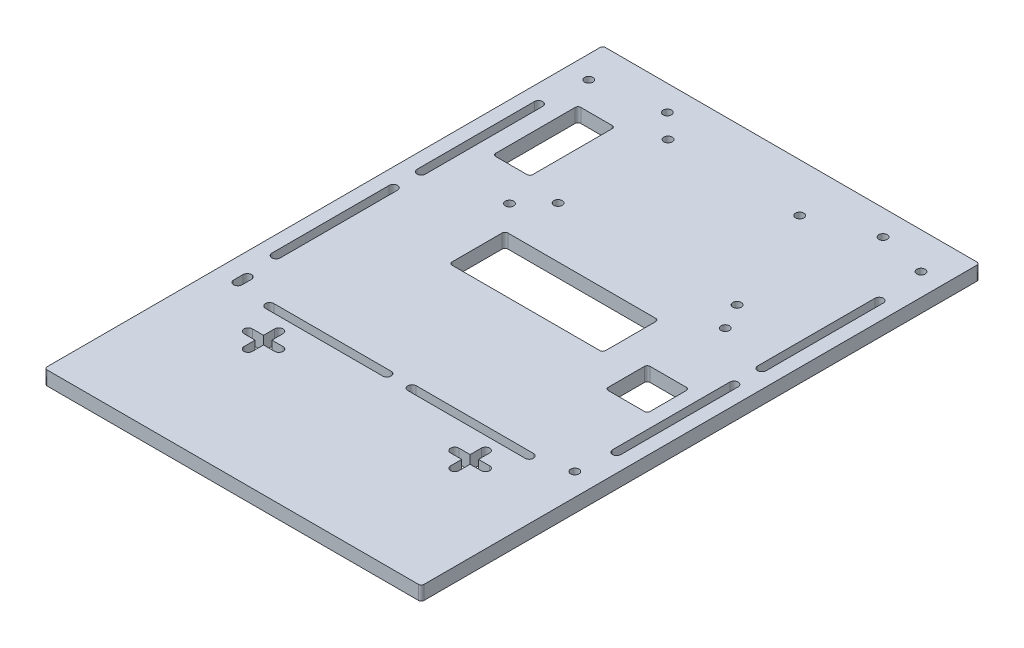
SolidWorks part; units mm, degrees
ref_plane "Front Plane" through (0, 0, 0) normal (0, 0, 1) x (1, 0, 0)
ref_plane "Top Plane" through (0, 0, 0) normal (0, 1, 0) x (1, 0, 0)
ref_plane "Right Plane" through (0, 0, 0) normal (1, 0, 0) x (0, 0, -1)
sketch "Sketch1" plane through (0, 0, 0) normal (0, 1, 0) x (1, 0, 0)
  line L1 (-67.4426, -147.7459) -> (65.5574, -147.7459)
  line L2 (-68.4426, -146.7459) -> (-68.4426, 51.2541)
  line L3 (-67.4426, 52.2541) -> (65.5574, 52.2541)
  line L4 (66.5574, -146.7459) -> (66.5574, 51.2541)
  arc A0 (-68.4426, -146.7459) -> (-67.4426, -147.7459) centre (-67.4426, -146.7459) ccw
  arc A1 (66.5574, -146.7459) -> (65.5574, -147.7459) centre (65.5574, -146.7459) cw
  arc A2 (66.5574, 51.2541) -> (65.5574, 52.2541) centre (65.5574, 51.2541) ccw
  arc A3 (-68.4426, 51.2541) -> (-67.4426, 52.2541) centre (-67.4426, 51.2541) cw
  point P7 (-68.4426, -147.7459)
  point P12 (66.5574, 52.2541)
  point P15 (-68.4426, 52.2541)
  dimension "D3" = 1
  dimension "D1" = 135
  dimension "D2" = 200
extrude "Boss-Extrude1" add sketch "Sketch1" along normal blind 5
sketch "Sketch2" plane through (0, 5, 0) normal (0, 1, 0) x (1, 0, 0)
  line L0 (60.0574, -71.2459) -> (60.0574, -29.2459) construction
  line L1 (58.5574, -71.2459) -> (58.5574, -29.2459)
  line L2 (61.5574, -71.2459) -> (61.5574, -29.2459)
  line L3 (66.5574, -146.7459) -> (66.5574, 51.2541) construction
  line L4 (65.5574, 52.2541) -> (-67.4426, 52.2541) construction
  line L5 (60.0574, -19.2459) -> (60.0574, 22.7541) construction
  line L8 (58.5574, -19.2459) -> (58.5574, 22.7541)
  line L10 (61.5574, -19.2459) -> (61.5574, 22.7541)
  line L13 (-61.9426, -71.2459) -> (-61.9426, -29.2459) construction
  line L14 (-60.4426, -71.2459) -> (-60.4426, -29.2459)
  line L15 (-63.4426, -71.2459) -> (-63.4426, -29.2459)
  line L16 (-61.9426, -19.2459) -> (-61.9426, 22.7541) construction
  line L17 (-60.4426, -19.2459) -> (-60.4426, 22.7541)
  line L18 (-63.4426, -19.2459) -> (-63.4426, 22.7541)
  arc A0 (58.5574, -71.2459) -> (61.5574, -71.2459) centre (60.0574, -71.2459) ccw
  arc A1 (61.5574, -29.2459) -> (58.5574, -29.2459) centre (60.0574, -29.2459) ccw
  arc A8 (58.5574, -19.2459) -> (61.5574, -19.2459) centre (60.0574, -19.2459) ccw
  arc A9 (61.5574, 22.7541) -> (58.5574, 22.7541) centre (60.0574, 22.7541) ccw
  arc A10 (-60.4426, -71.2459) -> (-63.4426, -71.2459) centre (-61.9426, -71.2459) cw
  arc A11 (-63.4426, -29.2459) -> (-60.4426, -29.2459) centre (-61.9426, -29.2459) cw
  arc A12 (-60.4426, -19.2459) -> (-63.4426, -19.2459) centre (-61.9426, -19.2459) cw
  arc A13 (-63.4426, 22.7541) -> (-60.4426, 22.7541) centre (-61.9426, 22.7541) cw
  point P2 (60.0574, -50.2459)
  point P9 (60.0574, -72.7459)
  point P14 (60.0574, 1.7541)
  point P19 (60.0574, -20.7459)
  point P20 (60.0574, -27.7459)
  point P21 (60.0574, 24.2541)
  point P28 (-61.9426, -50.2459)
  point P35 (-61.9426, 1.7541)
  dimension "D1" = 3
  dimension "D2" = 45
  dimension "D3" = 5
  dimension "D5" = 7
  dimension "D6" = 45
  dimension "D7" = 5
extrude "Cut-Extrude1" cut sketch "Sketch2" against normal blind 5
sketch "Sketch3" plane through (0, 5, 0) normal (0, 1, 0) x (1, 0, 0)
  line L0 (-47.4426, -88.0459) -> (-5.4426, -88.0459) construction
  line L1 (-47.4426, -86.5459) -> (-5.4426, -86.5459)
  line L2 (-47.4426, -89.5459) -> (-5.4426, -89.5459)
  line L4 (-68.4426, 51.2541) -> (-68.4426, -146.7459) construction
  line L5 (3.5574, -88.0459) -> (45.5574, -88.0459) construction
  line L6 (3.5574, -86.5459) -> (45.5574, -86.5459)
  line L7 (3.5574, -89.5459) -> (45.5574, -89.5459)
  line L9 (66.5574, -146.7459) -> (66.5574, 51.2541) construction
  arc A0 (-47.4426, -86.5459) -> (-47.4426, -89.5459) centre (-47.4426, -88.0459) ccw
  arc A1 (-5.4426, -89.5459) -> (-5.4426, -86.5459) centre (-5.4426, -88.0459) ccw
  arc A2 (3.5574, -86.5459) -> (3.5574, -89.5459) centre (3.5574, -88.0459) ccw
  arc A3 (45.5574, -89.5459) -> (45.5574, -86.5459) centre (45.5574, -88.0459) ccw
  point P2 (-26.4426, -88.0459)
  point P9 (-48.9426, -88.0459)
  point P14 (24.5574, -88.0459)
  point P21 (47.0574, -88.0459)
  dimension "D1" = 3
  dimension "D2" = 42
  dimension "D4" = 19.5
  dimension "D5" = 3
  dimension "D7" = 42
  dimension "D9" = 19.5
extrude "Cut-Extrude2" cut sketch "Sketch3" against normal blind 5
sketch "Sketch4" plane through (0, 5, 0) normal (0, 1, 0) x (1, 0, 0)
  line L0 (65.5574, 52.2541) -> (-67.4426, 52.2541) construction
  line L1 (-27.4426, -22.7459) -> (25.5574, -22.7459)
  line L2 (-28.4426, -23.7459) -> (-28.4426, -41.7459)
  line L3 (-27.4426, -42.7459) -> (25.5574, -42.7459)
  line L4 (26.5574, -23.7459) -> (26.5574, -41.7459)
  line L5 (66.5574, -146.7459) -> (66.5574, 51.2541) construction
  arc A0 (-28.4426, -41.7459) -> (-27.4426, -42.7459) centre (-27.4426, -41.7459) ccw
  arc A1 (25.5574, -42.7459) -> (26.5574, -41.7459) centre (25.5574, -41.7459) ccw
  arc A2 (25.5574, -22.7459) -> (26.5574, -23.7459) centre (25.5574, -23.7459) cw
  arc A3 (-27.4426, -22.7459) -> (-28.4426, -23.7459) centre (-27.4426, -23.7459) ccw
  point P11 (26.5574, -42.7459)
  point P15 (26.5574, -22.7459)
  point P18 (-28.4426, -22.7459)
  dimension "D1" = 1
  dimension "D2" = 20
  dimension "D3" = 55
  dimension "D4" = 40
sketch "Sketch5" plane through (0, 5, 0) normal (0, 1, 0) x (1, 0, 0)
  line L0 (66.5574, -146.7459) -> (66.5574, 51.2541) construction
  line L1 (-60.4426, -83.0689) -> (-60.4426, -86.4229) construction
  line L2 (-58.9426, -83.0689) -> (-58.9426, -86.4229)
  line L3 (-61.9426, -83.0689) -> (-61.9426, -86.4229)
  line L6 (-68.4426, 51.2541) -> (-68.4426, -146.7459) construction
  circle A0 centre (58.5574, -84.7459) radius 1.5
  circle A2 centre (58.5574, 39.2541) radius 1.5
  circle A3 centre (-60.4426, 39.2541) radius 1.5
  arc A4 (-58.9426, -83.0689) -> (-61.9426, -83.0689) centre (-60.4426, -83.0689) ccw
  arc A5 (-61.9426, -86.4229) -> (-58.9426, -86.4229) centre (-60.4426, -86.4229) ccw
  point P6 (-60.4426, -84.7459)
  dimension "D1" = 3
  dimension "D2" = 8
  dimension "D3" = 3
  dimension "D4" = 8
extrude "Cut-Extrude3" cut sketch "Sketch5" against normal blind 5
extrude "Cut-Extrude4" cut sketch "Sketch4" against normal blind 5
sketch "Sketch6" plane through (0, 5, 0) normal (0, 1, 0) x (1, 0, 0)
  line L30 (-53.3275, 29.2691) -> (-42.0865, 29.2691)
  line L34 (-54.3275, 28.2691) -> (-54.3275, -0.2046)
  line L45 (-53.3275, -1.2046) -> (-42.0865, -1.2046)
  line L46 (-41.0865, 28.2691) -> (-41.0865, -0.2046)
  line L47 (39.4163, -38.6556) -> (52.4163, -38.6556)
  line L48 (38.4163, -39.6556) -> (38.4163, -52.6556)
  line L49 (39.4163, -53.6556) -> (52.4163, -53.6556)
  line L50 (53.4163, -39.6556) -> (53.4163, -52.6556)
  arc A12 (-54.3275, -0.2046) -> (-53.3275, -1.2046) centre (-53.3275, -0.2046) ccw
  arc A13 (-41.0865, -0.2046) -> (-42.0865, -1.2046) centre (-42.0865, -0.2046) cw
  arc A14 (-42.0865, 29.2691) -> (-41.0865, 28.2691) centre (-42.0865, 28.2691) cw
  arc A15 (-53.3275, 29.2691) -> (-54.3275, 28.2691) centre (-53.3275, 28.2691) ccw
  arc A16 (53.4163, -52.6556) -> (52.4163, -53.6556) centre (52.4163, -52.6556) cw
  arc A17 (39.4163, -53.6556) -> (38.4163, -52.6556) centre (39.4163, -52.6556) cw
  arc A18 (39.4163, -38.6556) -> (38.4163, -39.6556) centre (39.4163, -39.6556) ccw
  arc A19 (52.4163, -38.6556) -> (53.4163, -39.6556) centre (52.4163, -39.6556) cw
  circle B0 centre (-36.2518, 43.1833) radius 1.5
  circle B1 centre (-36.2518, -13.3377) radius 1.5
  circle B2 centre (41.03, -13.3377) radius 1.5
  circle B3 centre (41.03, 43.1833) radius 1.5
  line B4 (37.5574, -94.2459) -> (37.5574, -98.2459)
  line B5 (-43.4426, -98.2459) -> (-39.4426, -98.2459)
  line B6 (-43.4426, -101.2459) -> (-39.4426, -101.2459)
  line B7 (-36.4426, -94.2459) -> (-36.4426, -98.2459)
  line B8 (-39.4426, -94.2459) -> (-39.4426, -98.2459)
  line B9 (-36.4426, -101.2459) -> (-36.4426, -105.2459)
  line B10 (-39.4426, -101.2459) -> (-39.4426, -105.2459)
  line B11 (-36.4426, -98.2459) -> (-32.4426, -98.2459)
  line B12 (-36.4426, -101.2459) -> (-32.4426, -101.2459)
  line B13 (41.5574, -98.2459) -> (37.5574, -98.2459)
  line B14 (41.5574, -101.2459) -> (37.5574, -101.2459)
  line B15 (37.5574, -101.2459) -> (37.5574, -105.2459)
  line B16 (34.5574, -101.2459) -> (34.5574, -105.2459)
  line B17 (34.5574, -101.2459) -> (30.5574, -101.2459)
  line B18 (34.5574, -98.2459) -> (30.5574, -98.2459)
  line B19 (34.5574, -94.2459) -> (34.5574, -98.2459)
  arc B20 (-43.4426, -98.2459) -> (-43.4426, -101.2459) centre (-43.4426, -99.7459) ccw
  arc B21 (-32.4426, -101.2459) -> (-32.4426, -98.2459) centre (-32.4426, -99.7459) ccw
  arc B22 (-36.4426, -94.2459) -> (-39.4426, -94.2459) centre (-37.9426, -94.2459) ccw
  arc B23 (-39.4426, -105.2459) -> (-36.4426, -105.2459) centre (-37.9426, -105.2459) ccw
  arc B24 (34.5574, -94.2459) -> (37.5574, -94.2459) centre (36.0574, -94.2459) cw
  arc B25 (41.5574, -98.2459) -> (41.5574, -101.2459) centre (41.5574, -99.7459) cw
  arc B26 (37.5574, -105.2459) -> (34.5574, -105.2459) centre (36.0574, -105.2459) cw
  arc B27 (30.5574, -101.2459) -> (30.5574, -98.2459) centre (30.5574, -99.7459) cw
  dimension "D1" = 1
  dimension "D2" = 1
  dimension "D3" = 15
  dimension "D4" = 15
sketch_block_instance "STMboard-1"
sketch_block "STMboard" parameters "D1"=95.745, "D2"=56.521
sketch_block_instance "JetsonNano-1"
sketch_block "JetsonNano" parameters "D1"=11, "D2"=3, "D3"=11
extrude "Cut-Extrude5" cut sketch "Sketch6" against normal blind 5
sketch "Sketch7" plane through (0, 5, 0) normal (0, 1, 0) x (1, 0, 0)
  circle A0 centre (-27.7426, -4.4396) radius 1.5
  circle A1 centre (35.9254, -3.9996) radius 1.5
  circle A2 centre (-27.7426, 34.9374) radius 1.5
  circle A3 centre (19.4344, 34.9374) radius 1.5
  point P8 (0, 0)
  point P9 (0, 0)
  point P10 (-27.7426, 34.9374)
  dimension "D1" = 39.377
  dimension "D2" = 47.177
  dimension "D3" = 63.668
  dimension "D4" = 0.44
extrude "Cut-Extrude6" cut sketch "Sketch7" against normal blind 10
